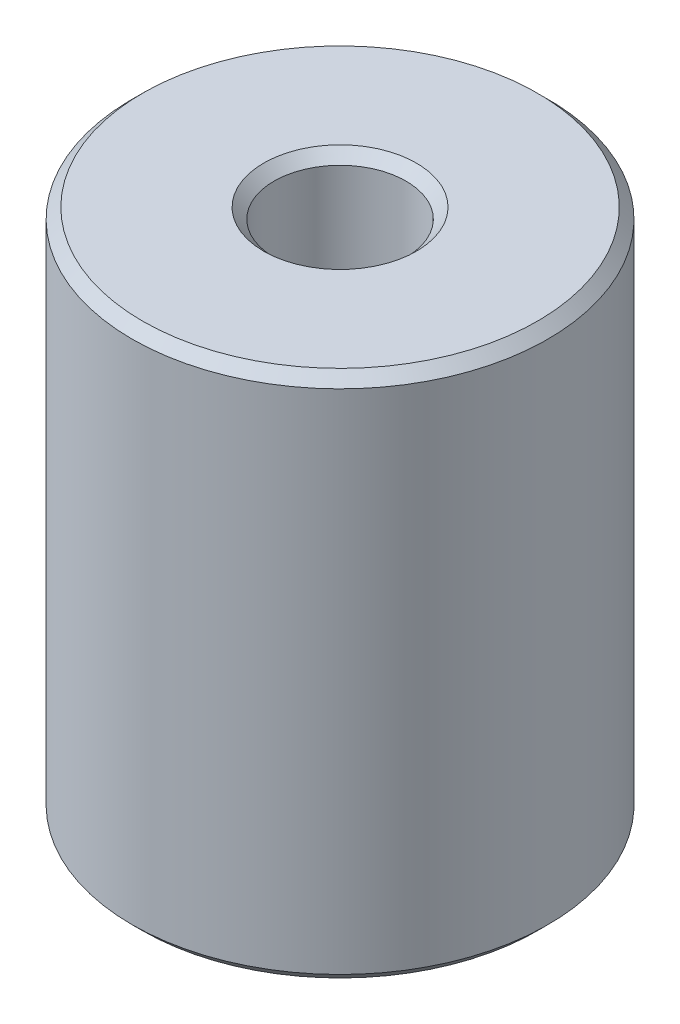
SolidWorks part; units mm, degrees
ref_plane "Front Plane" through (0, 0, 0) normal (0, 0, 1) x (1, 0, 0)
ref_plane "Top Plane" through (0, 0, 0) normal (0, 1, 0) x (1, 0, 0)
ref_plane "Right Plane" through (0, 0, 0) normal (1, 0, 0) x (0, 0, -1)
sketch "Sketch2" plane through (0, 0, 0) normal (0, 1, 0) x (1, 0, 0)
  circle A0 centre (0, 0) radius 10
  dimension "D1" = 20
extrude "Boss-Extrude1" add sketch "Sketch2" along normal blind 25.4
sketch "Sketch3" plane through (0, 25.4, 0) normal (0, 1, 0) x (1, 0, 0)
  circle A0 centre (0, 0) radius 3.175
extrude "Cut-Extrude1" cut sketch "Sketch3" against normal blind 12.7
chamfer "Chamfer1" distance 0.5 angle 45 3 edges at (0, 25.4, 10) (0, 0, 10) (0, 25.4, 3.175)
sketch "Sketch4" plane through (0, 0, 0) normal (0, -1, 0) x (1, 0, 0)
  circle A0 centre (0, 0) radius 4
extrude "Cut-Extrude2" cut sketch "Sketch4" against normal blind 12.7
